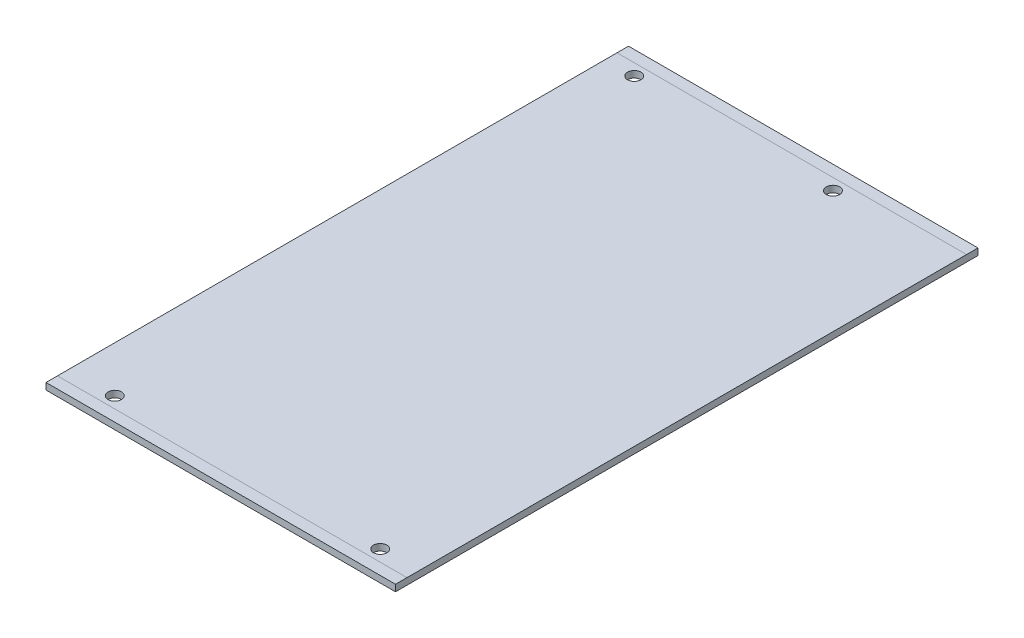
SolidWorks part; units mm, degrees
ref_plane "Front Plane" through (0, 0, 0) normal (0, 0, 1) x (1, 0, 0)
ref_plane "Top Plane" through (0, 0, 0) normal (0, 1, 0) x (1, 0, 0)
ref_plane "Right Plane" through (0, 0, 0) normal (1, 0, 0) x (0, 0, -1)
sketch "Sketch1" plane through (0, 0, 0) normal (0, 1, 0) x (1, 0, 0)
  line L1 (-45.72, -76.2) -> (45.72, -76.2)
  line L2 (-45.72, -76.2) -> (-45.72, 76.2)
  line L3 (-45.72, 76.2) -> (45.72, 76.2)
  line L4 (45.72, -76.2) -> (45.72, 76.2)
  line L5 (-45.72, -76.2) -> (45.72, 76.2) construction
  line L6 (-45.72, 76.2) -> (45.72, -76.2) construction
  point P0 (0, 0)
  dimension "D1" = 91.44
  dimension "D2" = 152.4
extrude "Boss-Extrude1" add sketch "Sketch1" along normal blind 1.724
sketch "Sketch2" plane through (0, 1.724, 0) normal (0, 1, 0) x (1, 0, 0)
  line L0 (-45.72, 76.2) -> (-45.72, -76.2) construction
  line L1 (-45.72, -76.2) -> (45.72, -76.2) construction
  line L2 (45.72, 76.2) -> (-45.72, 76.2) construction
  line L3 (45.72, 76.2) -> (-45.72, 76.2) construction
  line L5 (45.72, -76.2) -> (45.72, 76.2) construction
  circle A0 centre (-38.22, 70.2) radius 1.75
  circle A1 centre (-33.72, -70.2) radius 1.75
  circle A2 centre (35.72, -70.2) radius 1.75
  circle A3 centre (13.78, 70.2) radius 1.75
  dimension "D4" = 12
  dimension "D5" = 3.5
  dimension "D6" = 3.5
  dimension "D8" = 6
  dimension "D9" = 10
  dimension "D10" = 7.5
  dimension "D2" = 6
  dimension "D3" = 3.5
  dimension "D11" = 3.5
  dimension "D12" = 6
  dimension "D13" = 52
  dimension "D7" = 6
extrude "Cut-Extrude1" cut sketch "Sketch2" against normal up to next
sketch "Sketch3" plane through (0, 1.724, 0) normal (0, 1, 0) x (1, 0, 0)
  line L0 (45.72, -76.2) -> (45.72, 76.2) construction
  line L1 (-45.72, 76.2) -> (45.72, 76.2)
  line L2 (-45.72, 76.2) -> (-45.72, 73.2)
  line L3 (-45.72, 73.2) -> (45.72, 73.2)
  line L4 (45.72, 76.2) -> (45.72, 73.2)
  line L6 (-45.72, -76.2) -> (45.72, -76.2)
  line L7 (-45.72, -76.2) -> (-45.72, -73.2)
  line L8 (-45.72, -73.2) -> (45.72, -73.2)
  line L9 (45.72, -76.2) -> (45.72, -73.2)
  dimension "D1" = 3
  dimension "D2" = 3
extrude "Cut-Extrude2" cut sketch "Sketch3" against normal blind 0.0001
